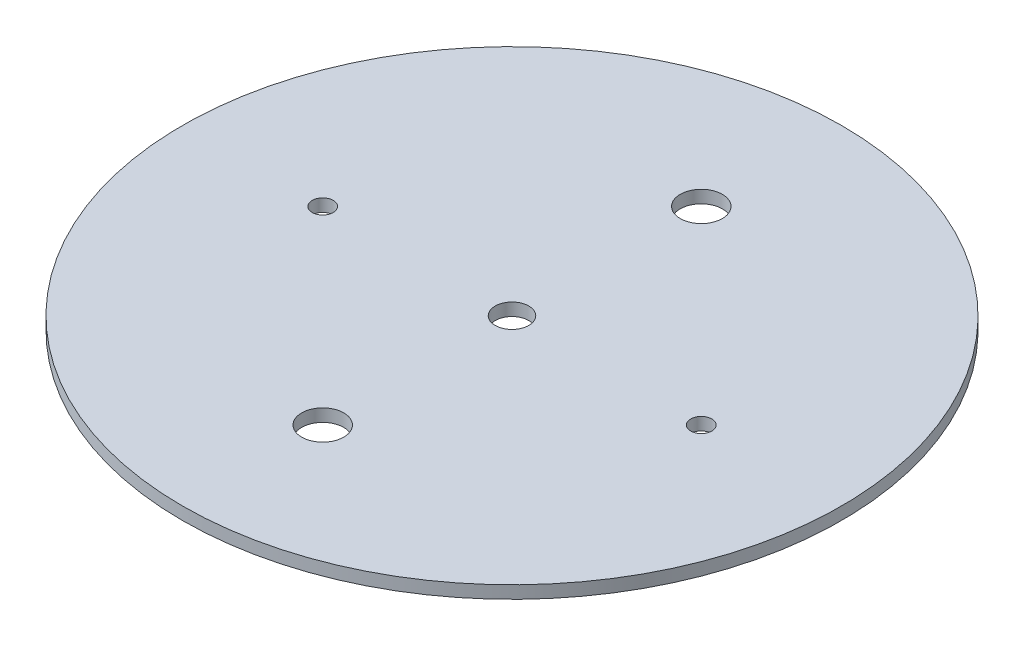
SolidWorks part; units mm, degrees
ref_plane "Front Plane" through (0, 0, 0) normal (0, 0, 1) x (1, 0, 0)
ref_plane "Top Plane" through (0, 0, 0) normal (0, 1, 0) x (1, 0, 0)
ref_plane "Right Plane" through (0, 0, 0) normal (1, 0, 0) x (0, 0, -1)
sketch "Sketch1" plane through (0, 0, 0) normal (0, 1, 0) x (1, 0, 0)
  line L0 (45, 0) -> (-45, 0) construction
  line L1 (0, -45) -> (0, 0) construction
  circle A0 centre (0, 0) radius 78.35
  circle A1 centre (-45, 0) radius 2.5
  circle A2 centre (45, 0) radius 2.5
  circle A3 centre (0, 0) radius 4
  circle A4 centre (0, -45) radius 5
  circle A5 centre (0, 45) radius 5
  point P6 (0, 0)
  dimension "D1" = 156.7
  dimension "D2" = 5
  dimension "D3" = 5
  dimension "D5" = 8
  dimension "D6" = 10
  dimension "D4" = 90
  dimension "D7" = 45
extrude "Boss-Extrude1" add sketch "Sketch1" along normal blind 3
